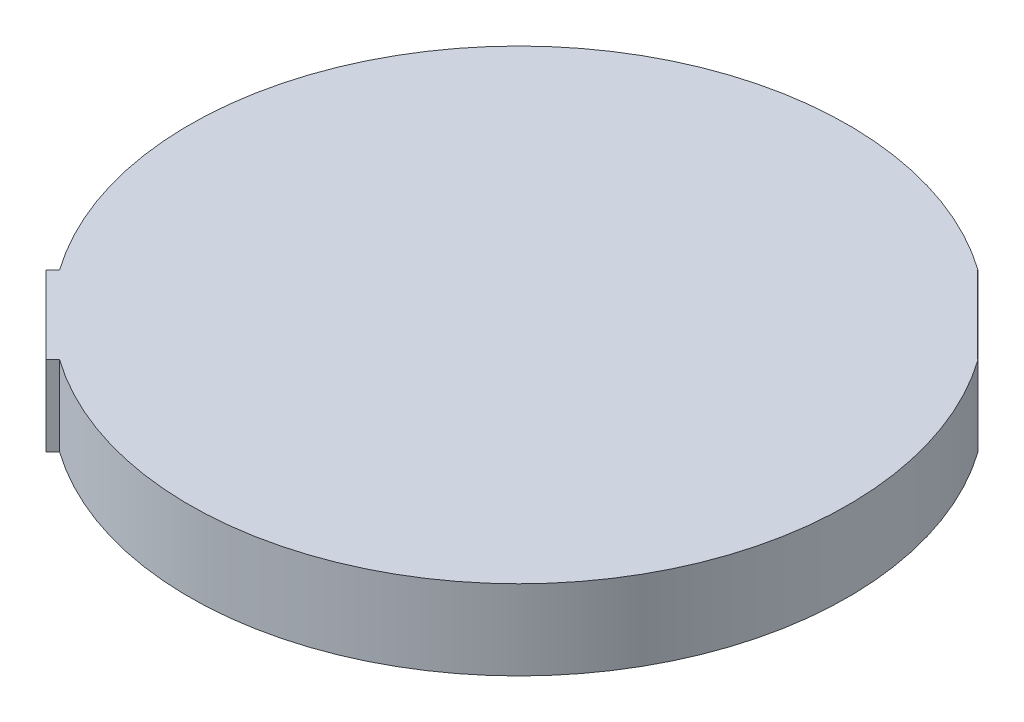
SolidWorks part; units mm, degrees
ref_plane "Front Plane" through (0, 0, 0) normal (0, 0, 1) x (1, 0, 0)
ref_plane "Top Plane" through (0, 0, 0) normal (0, 1, 0) x (1, 0, 0)
ref_plane "Right Plane" through (0, 0, 0) normal (1, 0, 0) x (0, 0, -1)
sketch "Sketch1" plane through (0, 0, 0) normal (0, 1, 0) x (1, 0, 0)
  circle A0 centre (0, 0) radius 330
  dimension "D1" = 660
extrude "Boss-Extrude1" add sketch "Sketch1" along normal blind 80
sketch "Sketch2" plane through (0, 80, 0) normal (0, 1, 0) x (1, 0, 0)
  line L0 (0, 330) -> (0, -330) construction
  line L1 (-330, 0) -> (330, 0) construction
  circle A0 centre (0, 0) radius 330 construction
  point P7 (0, 0)
sketch "Sketch3" plane through (0, 80, 0) normal (0, 1, 0) x (1, 0, 0)
  line L0 (0, 330) -> (0, -330) construction
  line L1 (-330, 0) -> (330, 0) construction
  line L2 (0, 0) -> (-233.3452, -233.3452) construction
  line L3 (0, 0) -> (-233.3452, 233.3452) construction
  circle A0 centre (0, 0) radius 330 construction
  dimension "D1" = 45
  dimension "D2" = 45
sketch "Sketch4" plane through (0, 80, 0) normal (0, 1, 0) x (1, 0, 0)
  line L0 (0, 0) -> (-233.3452, -233.3452) construction
  line L6 (-342.9468, -265.165) -> (-265.165, -342.9468)
  line L7 (-342.9468, -265.165) -> (-265.165, -187.3833)
  line L8 (-265.165, -187.3833) -> (-187.3833, -265.165)
  line L9 (-265.165, -342.9468) -> (-187.3833, -265.165)
  point P4 (-226.2742, -226.2742)
  dimension "D1" = 110
  dimension "D2" = 10
  dimension "D3" = 110
extrude "Cut-Extrude1" [suppressed] cut sketch "Sketch4" against normal through all both and the other way through all
sketch "Sketch5" [suppressed] plane through (0, 60, 0) normal (0, 1, 0) x (1, 0, 0)
  line L0 (-187.3833, -265.165) -> (-265.165, -187.3833)
  line L1 (-265.165, -187.3833) -> (-229.8097, -152.028)
  line L2 (-229.8097, -152.028) -> (-152.028, -229.8097)
  line L3 (-152.028, -229.8097) -> (-187.3833, -265.165)
  line L4 (-279.3072, -201.5254) -> (-283.3034, -205.5217) construction
  line L5 (-205.5217, -283.3034) -> (-201.5254, -279.3072) construction
  line L6 (-201.5254, -279.3072) -> (-279.3072, -201.5254) construction
  dimension "D1" = 50
  dimension "D2" = 20
extrude "Cut-Extrude2" [suppressed] cut sketch "Sketch5" against normal through all both and the other way through all
sketch "Sketch6" plane through (0, 80, 0) normal (0, 1, 0) x (1, 0, 0)
  line L0 (-194.4544, -272.2361) -> (-272.2361, -194.4544) construction
  line L1 (-272.2361, -194.4544) -> (-275.7716, -197.9899)
  line L2 (-275.7716, -197.9899) -> (-197.9899, -275.7716)
  line L3 (-197.9899, -275.7716) -> (-194.4544, -272.2361)
  line L4 (-233.3452, -233.3452) -> (-122.6562, -233.3452) construction
  line L5 (-272.2361, -194.4544) -> (-268.9724, -191.1906)
  line L6 (-194.4544, -272.2361) -> (-191.1906, -268.9724)
  circle A0 centre (0, 0) radius 330 construction
  arc A1 (-268.9724, -191.1906) -> (-191.1906, -268.9724) centre (0, 0) ccw
  point P0 (-233.3452, -233.3452)
  dimension "D1" = 110
  dimension "D2" = 5
  dimension "D3" = 45
extrude "Boss-Extrude2" add sketch "Sketch6" against normal up to surface (80 mm away) up to face at (0, 0, 330)
ref_plane "Plane1" through (229.8097, 0, -229.8097) normal (-0.7071, 0, 0.7071) x (0.7071, 0, 0.7071)
sketch "Sketch7" plane through (229.8097, 0, -229.8097) normal (-0.7071, 0, 0.7071) x (0.7071, 0, 0.7071)
  line L4 (-55, 0) -> (55, 0)
  line L5 (55, 0) -> (55, 80)
  line L6 (55, 80) -> (-55, 80)
  line L7 (-55, 80) -> (-55, 0)
  line L8 (-55, 0) -> (55, 0)
  line L9 (55, 0) -> (55, 80)
  line L10 (55, 80) -> (-55, 80)
  line L11 (-55, 80) -> (-55, 0)
  dimension "D1" = 0
extrude "Boss-Extrude3" add sketch "Sketch7" along normal up to surface (650.3844 mm away)
sketch "Sketch9" plane through (229.8097, 0, -229.8097) normal (-0.7071, 0, 0.7071) x (0.7071, 0, 0.7071)
  line L4 (-55, 0) -> (55, 0)
  line L5 (55, 0) -> (55, 80)
  line L6 (55, 80) -> (-55, 80)
  line L7 (-55, 80) -> (-55, 0)
  line L8 (-55, 0) -> (55, 0)
  line L9 (55, 0) -> (55, 80)
  line L10 (55, 80) -> (-55, 80)
  line L11 (-55, 80) -> (-55, 0)
  dimension "D1" = 0
extrude "Cut-Extrude4" cut sketch "Sketch9" against normal blind 12
sketch "Sketch10" plane through (229.8097, 0, -229.8097) normal (0.7071, 0, -0.7071) x (-0.7071, 0, -0.7071)
  line L0 (0, 80) -> (0, 0) construction
  line L1 (0, 80) -> (330, 80) construction
  line L2 (55, 0) -> (-55, 0) construction
  circle A0 centre (0, 40) radius 31
  dimension "D1" = 62
extrude "Cut-Extrude5" cut sketch "Sketch10" against normal blind 13
sketch "Sketch11" plane through (0, 80, 0) normal (0, 1, 0) x (1, 0, 0)
  point P4 (-233.3452, -233.3452)
sketch "Sketch12" plane through (0, 80, 0) normal (0, 1, 0) x (1, 0, 0)
  circle A0 centre (0, 0) radius 330
  point P3 (-233.3452, -233.3452)
ref_plane "Plane2" through (0, 40, 0) normal (0, 1, 0) x (1, 0, 0)
sketch "Sketch13" plane through (0, 40, 0) normal (0, 1, 0) x (1, 0, 0)
  line L0 (-236.8808, -236.8808) -> (229.8097, 229.8097) construction
  line L1 (-275.7716, -197.9899) -> (-197.9899, -275.7716) construction
  line L2 (268.7006, 190.9188) -> (190.9188, 268.7006) construction
sketch "Sketch14" plane through (-236.8808, 0, 236.8808) normal (-0.7071, 0, 0.7071) x (0.7071, 0, 0.7071)
  line L0 (0, 0) -> (0, 80) construction
  line L1 (-55, 80) -> (55, 80) construction
  circle A0 centre (0, 40) radius 21 construction
  point P8 (0, 40)
  dimension "D1" = 42
